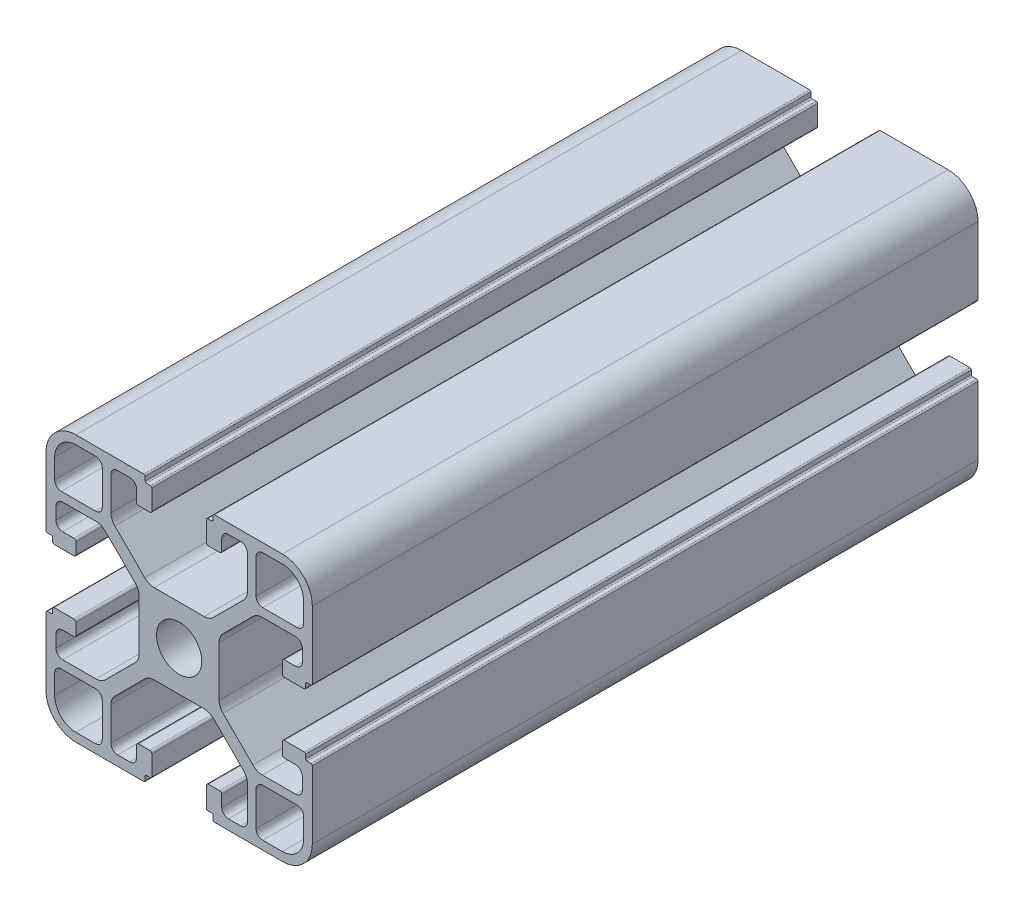
SolidWorks part; units mm, degrees
material "6063-T5"
ref_plane "Front Plane" through (0, 0, 0) normal (0, 0, 1) x (1, 0, 0)
ref_plane "Top Plane" through (0, 0, 0) normal (0, 1, 0) x (1, 0, 0)
ref_plane "Right Plane" through (0, 0, 0) normal (1, 0, 0) x (0, 0, -1)
sketch "Sketch2" plane through (0, 0, 0) normal (0, 0, 1) x (1, 0, 0)
  line L0 (4.5, 0) -> (14.7, 0)
  line L1 (40, 4.5) -> (40, 14.7)
  line L2 (35.5, 40) -> (25.3, 40)
  line L3 (0, 35.5) -> (0, 25.3)
  line L4 (15.9, 1.2) -> (15.9, 4.2)
  line L5 (24.1, 1.2) -> (24.1, 4.2)
  line L6 (38.8, 24.1) -> (35.8, 24.1)
  line L7 (35.5, 24.4) -> (35.5, 26.1)
  line L8 (14, 23.7574) -> (14, 16.2426)
  line L9 (16.2426, 14) -> (23.7574, 14)
  line L10 (26, 16.2426) -> (26, 23.7574)
  line L11 (13.4142, 14.8284) -> (8.9216, 10.3358)
  line L12 (23.7574, 26) -> (16.2426, 26)
  line L13 (4.5, 24.4) -> (4.5, 26.1)
  line L14 (1.2, 24.1) -> (4.2, 24.1)
  line L15 (15.9, 38.8) -> (15.9, 35.8)
  line L16 (14.8284, 26.5858) -> (10.3358, 31.0784)
  line L17 (13.4142, 25.1716) -> (8.9216, 29.6642)
  line L18 (14.8284, 13.4142) -> (10.3358, 8.9216)
  line L19 (25.1716, 13.4142) -> (29.6642, 8.9216)
  line L20 (26.5858, 14.8284) -> (31.0784, 10.3358)
  line L21 (26.5858, 25.1716) -> (31.0784, 29.6642)
  line L22 (25.1716, 26.5858) -> (29.6642, 31.0784)
  line L23 (24.1, 38.8) -> (24.1, 35.8)
  line L24 (14.7, 40) -> (4.5, 40)
  line L25 (25.3, 0) -> (35.5, 0)
  line L26 (38.8, 15.9) -> (35.8, 15.9)
  line L27 (40, 25.3) -> (40, 35.5)
  line L28 (1.2, 15.9) -> (4.2, 15.9)
  line L29 (0, 14.7) -> (0, 4.5)
  line L30 (4.5, 15.6) -> (4.5, 13.9)
  line L31 (35.5, 15.6) -> (35.5, 13.9)
  line L32 (15.6, 35.5) -> (13.9, 35.5)
  line L33 (24.4, 35.5) -> (26.1, 35.5)
  line L34 (15.6, 4.5) -> (13.9, 4.5)
  line L35 (24.4, 4.5) -> (26.1, 4.5)
  line L36 (12.6, 38.5) -> (10.75, 38.5)
  line L37 (1.5, 12.6) -> (1.5, 10.75)
  line L38 (27.4, 1.5) -> (29.25, 1.5)
  line L39 (38.5, 27.4) -> (38.5, 29.25)
  line L40 (38.5, 10.75) -> (38.5, 12.6)
  line L41 (29.25, 38.5) -> (27.4, 38.5)
  line L42 (1.5, 29.25) -> (1.5, 27.4)
  line L43 (10.75, 1.5) -> (12.6, 1.5)
  line L44 (35.8, 26.4) -> (37.5, 26.4)
  line L45 (35.8, 13.6) -> (37.5, 13.6)
  line L46 (4.2, 26.4) -> (2.5, 26.4)
  line L47 (13.6, 35.8) -> (13.6, 37.5)
  line L48 (26.4, 35.8) -> (26.4, 37.5)
  line L49 (4.2, 13.6) -> (2.5, 13.6)
  line L50 (13.6, 4.2) -> (13.6, 2.5)
  line L51 (26.4, 4.2) -> (26.4, 2.5)
  line L52 (9.75, 7.5074) -> (9.75, 2.5)
  line L53 (30.25, 7.5074) -> (30.25, 2.5)
  line L54 (9.75, 37.5) -> (9.75, 32.4926)
  line L55 (30.25, 37.5) -> (30.25, 32.4926)
  line L56 (32.4926, 30.25) -> (37.5, 30.25)
  line L57 (37.5, 9.75) -> (32.4926, 9.75)
  line L58 (2.5, 30.25) -> (7.5074, 30.25)
  line L59 (2.5, 9.75) -> (7.5074, 9.75)
  line L60 (31.55, 37.7) -> (31.55, 32.55)
  line L61 (32.55, 31.55) -> (37.7, 31.55)
  line L62 (1.3, 35.5) -> (1.3, 32.55)
  line L63 (4.5, 38.7) -> (7.45, 38.7)
  line L64 (32.55, 38.7) -> (35.5, 38.7)
  line L65 (38.7, 35.5) -> (38.7, 32.55)
  line L66 (8.45, 37.7) -> (8.45, 32.55)
  line L67 (2.3, 31.55) -> (7.45, 31.55)
  line L68 (1.3, 7.45) -> (1.3, 4.5)
  line L69 (2.3, 8.45) -> (7.45, 8.45)
  line L70 (8.45, 7.45) -> (8.45, 2.3)
  line L71 (4.5, 1.3) -> (7.45, 1.3)
  line L72 (31.55, 7.45) -> (31.55, 2.3)
  line L73 (32.55, 8.45) -> (37.7, 8.45)
  line L74 (38.7, 7.45) -> (38.7, 4.5)
  line L75 (32.55, 1.3) -> (35.5, 1.3)
  line L77 (14.9, 39.8) -> (14.9, 39.2)
  line L78 (15.1, 39) -> (15.7, 39)
  line L79 (25.1, 39.8) -> (25.1, 39.2)
  line L80 (24.9, 39) -> (24.3, 39)
  line L81 (25.1, 0.2) -> (25.1, 0.8)
  line L82 (24.9, 1) -> (24.3, 1)
  line L83 (14.9, 0.2) -> (14.9, 0.8)
  line L84 (15.1, 1) -> (15.7, 1)
  line L85 (0.2, 25.1) -> (0.8, 25.1)
  line L86 (1, 24.9) -> (1, 24.3)
  line L87 (0.2, 14.9) -> (0.8, 14.9)
  line L88 (1, 15.1) -> (1, 15.7)
  line L89 (39.8, 25.1) -> (39.2, 25.1)
  line L90 (39, 24.9) -> (39, 24.3)
  line L91 (39, 15.7) -> (39, 15.1)
  line L92 (39.2, 14.9) -> (39.8, 14.9)
  circle A0 centre (20, 20) radius 3.4
  arc A1 (1.3, 35.5) -> (4.5, 38.7) centre (4.5, 35.5) cw
  arc A2 (1.3, 4.5) -> (4.5, 1.3) centre (4.5, 4.5) ccw
  arc A3 (38.7, 4.5) -> (35.5, 1.3) centre (35.5, 4.5) cw
  arc A4 (35.5, 38.7) -> (38.7, 35.5) centre (35.5, 35.5) cw
  arc A5 (40, 35.5) -> (35.5, 40) centre (35.5, 35.5) ccw
  arc A6 (35.5, 0) -> (40, 4.5) centre (35.5, 4.5) ccw
  arc A7 (4.5, 0) -> (0, 4.5) centre (4.5, 4.5) cw
  arc A8 (4.5, 40) -> (0, 35.5) centre (4.5, 35.5) ccw
  arc A9 (13.4142, 14.8284) -> (14, 16.2426) centre (12, 16.2426) ccw
  arc A10 (7.5074, 9.75) -> (8.9216, 10.3358) centre (7.5074, 11.75) ccw
  arc A11 (9.75, 7.5074) -> (10.3358, 8.9216) centre (11.75, 7.5074) cw
  arc A12 (30.25, 7.5074) -> (29.6642, 8.9216) centre (28.25, 7.5074) ccw
  arc A13 (14.8284, 13.4142) -> (16.2426, 14) centre (16.2426, 12) cw
  arc A14 (25.1716, 13.4142) -> (23.7574, 14) centre (23.7574, 12) ccw
  arc A15 (32.4926, 9.75) -> (31.0784, 10.3358) centre (32.4926, 11.75) cw
  arc A16 (26.5858, 14.8284) -> (26, 16.2426) centre (28, 16.2426) cw
  arc A17 (32.4926, 30.25) -> (31.0784, 29.6642) centre (32.4926, 28.25) ccw
  arc A18 (26.5858, 25.1716) -> (26, 23.7574) centre (28, 23.7574) ccw
  arc A19 (13.4142, 25.1716) -> (14, 23.7574) centre (12, 23.7574) cw
  arc A20 (7.5074, 30.25) -> (8.9216, 29.6642) centre (7.5074, 28.25) cw
  arc A21 (9.75, 32.4926) -> (10.3358, 31.0784) centre (11.75, 32.4926) ccw
  arc A22 (30.25, 32.4926) -> (29.6642, 31.0784) centre (28.25, 32.4926) cw
  arc A23 (25.1716, 26.5858) -> (23.7574, 26) centre (23.7574, 28) cw
  arc A24 (14.8284, 26.5858) -> (16.2426, 26) centre (16.2426, 28) ccw
  arc A25 (37.7, 8.45) -> (38.7, 7.45) centre (37.7, 7.45) cw
  arc A26 (31.55, 2.3) -> (32.55, 1.3) centre (32.55, 2.3) ccw
  arc A27 (31.55, 7.45) -> (32.55, 8.45) centre (32.55, 7.45) cw
  arc A28 (8.45, 2.3) -> (7.45, 1.3) centre (7.45, 2.3) cw
  arc A29 (1.3, 7.45) -> (2.3, 8.45) centre (2.3, 7.45) cw
  arc A30 (7.45, 8.45) -> (8.45, 7.45) centre (7.45, 7.45) cw
  arc A31 (38.7, 32.55) -> (37.7, 31.55) centre (37.7, 32.55) cw
  arc A32 (31.55, 32.55) -> (32.55, 31.55) centre (32.55, 32.55) ccw
  arc A33 (31.55, 37.7) -> (32.55, 38.7) centre (32.55, 37.7) cw
  arc A34 (7.45, 38.7) -> (8.45, 37.7) centre (7.45, 37.7) cw
  arc A35 (8.45, 32.55) -> (7.45, 31.55) centre (7.45, 32.55) cw
  arc A36 (1.3, 32.55) -> (2.3, 31.55) centre (2.3, 32.55) ccw
  arc A37 (30.25, 2.5) -> (29.25, 1.5) centre (29.25, 2.5) cw
  arc A38 (26.4, 2.5) -> (27.4, 1.5) centre (27.4, 2.5) ccw
  arc A39 (13.6, 2.5) -> (12.6, 1.5) centre (12.6, 2.5) cw
  arc A40 (9.75, 2.5) -> (10.75, 1.5) centre (10.75, 2.5) ccw
  arc A41 (26.4, 37.5) -> (27.4, 38.5) centre (27.4, 37.5) cw
  arc A42 (30.25, 37.5) -> (29.25, 38.5) centre (29.25, 37.5) ccw
  arc A43 (37.5, 26.4) -> (38.5, 27.4) centre (37.5, 27.4) ccw
  arc A44 (37.5, 30.25) -> (38.5, 29.25) centre (37.5, 29.25) cw
  arc A45 (37.5, 13.6) -> (38.5, 12.6) centre (37.5, 12.6) cw
  arc A46 (37.5, 9.75) -> (38.5, 10.75) centre (37.5, 10.75) ccw
  arc A47 (2.5, 9.75) -> (1.5, 10.75) centre (2.5, 10.75) cw
  arc A48 (2.5, 13.6) -> (1.5, 12.6) centre (2.5, 12.6) ccw
  arc A49 (2.5, 26.4) -> (1.5, 27.4) centre (2.5, 27.4) cw
  arc A50 (2.5, 30.25) -> (1.5, 29.25) centre (2.5, 29.25) ccw
  arc A51 (9.75, 37.5) -> (10.75, 38.5) centre (10.75, 37.5) cw
  arc A52 (13.6, 37.5) -> (12.6, 38.5) centre (12.6, 37.5) ccw
  arc A53 (26.1, 35.5) -> (26.4, 35.8) centre (26.1, 35.8) ccw
  arc A54 (24.1, 35.8) -> (24.4, 35.5) centre (24.4, 35.8) ccw
  arc A55 (15.9, 35.8) -> (15.6, 35.5) centre (15.6, 35.8) cw
  arc A56 (13.9, 35.5) -> (13.6, 35.8) centre (13.9, 35.8) cw
  arc A57 (13.9, 4.5) -> (13.6, 4.2) centre (13.9, 4.2) ccw
  arc A58 (15.9, 4.2) -> (15.6, 4.5) centre (15.6, 4.2) ccw
  arc A59 (24.1, 4.2) -> (24.4, 4.5) centre (24.4, 4.2) cw
  arc A60 (26.1, 4.5) -> (26.4, 4.2) centre (26.1, 4.2) cw
  arc A61 (35.5, 13.9) -> (35.8, 13.6) centre (35.8, 13.9) ccw
  arc A62 (35.8, 15.9) -> (35.5, 15.6) centre (35.8, 15.6) ccw
  arc A63 (35.8, 24.1) -> (35.5, 24.4) centre (35.8, 24.4) cw
  arc A64 (35.5, 26.1) -> (35.8, 26.4) centre (35.8, 26.1) cw
  arc A65 (4.5, 13.9) -> (4.2, 13.6) centre (4.2, 13.9) cw
  arc A66 (4.2, 15.9) -> (4.5, 15.6) centre (4.2, 15.6) cw
  arc A67 (4.2, 24.1) -> (4.5, 24.4) centre (4.2, 24.4) ccw
  arc A68 (4.5, 26.1) -> (4.2, 26.4) centre (4.2, 26.1) ccw
  arc A69 (25.3, 0) -> (25.1, 0.2) centre (25.3, 0.2) cw
  arc A70 (25.1, 0.8) -> (24.9, 1) centre (24.9, 0.8) ccw
  arc A71 (24.3, 1) -> (24.1, 1.2) centre (24.3, 1.2) cw
  arc A72 (14.7, 0) -> (14.9, 0.2) centre (14.7, 0.2) ccw
  arc A73 (14.9, 0.8) -> (15.1, 1) centre (15.1, 0.8) cw
  arc A74 (15.7, 1) -> (15.9, 1.2) centre (15.7, 1.2) ccw
  arc A75 (39.8, 14.9) -> (40, 14.7) centre (39.8, 14.7) cw
  arc A76 (39, 15.1) -> (39.2, 14.9) centre (39.2, 15.1) ccw
  arc A77 (38.8, 15.9) -> (39, 15.7) centre (38.8, 15.7) cw
  arc A78 (0, 25.3) -> (0.2, 25.1) centre (0.2, 25.3) ccw
  arc A79 (0.8, 25.1) -> (1, 24.9) centre (0.8, 24.9) cw
  arc A80 (1, 24.3) -> (1.2, 24.1) centre (1.2, 24.3) ccw
  arc A81 (0, 14.7) -> (0.2, 14.9) centre (0.2, 14.7) cw
  arc A82 (0.8, 14.9) -> (1, 15.1) centre (0.8, 15.1) ccw
  arc A83 (1, 15.7) -> (1.2, 15.9) centre (1.2, 15.7) cw
  arc A84 (39, 24.3) -> (38.8, 24.1) centre (38.8, 24.3) cw
  arc A85 (39.2, 25.1) -> (39, 24.9) centre (39.2, 24.9) ccw
  arc A86 (40, 25.3) -> (39.8, 25.1) centre (39.8, 25.3) cw
  arc A87 (24.3, 39) -> (24.1, 38.8) centre (24.3, 38.8) ccw
  arc A88 (25.1, 39.2) -> (24.9, 39) centre (24.9, 39.2) cw
  arc A89 (25.3, 40) -> (25.1, 39.8) centre (25.3, 39.8) ccw
  arc A90 (14.9, 39.2) -> (15.1, 39) centre (15.1, 39.2) ccw
  arc A91 (15.7, 39) -> (15.9, 38.8) centre (15.7, 38.8) cw
  arc A92 (14.7, 40) -> (14.9, 39.8) centre (14.7, 39.8) cw
  point P93 (0, 0)
extrude "Boss-Extrude1" add sketch "Sketch2" along normal blind 100
